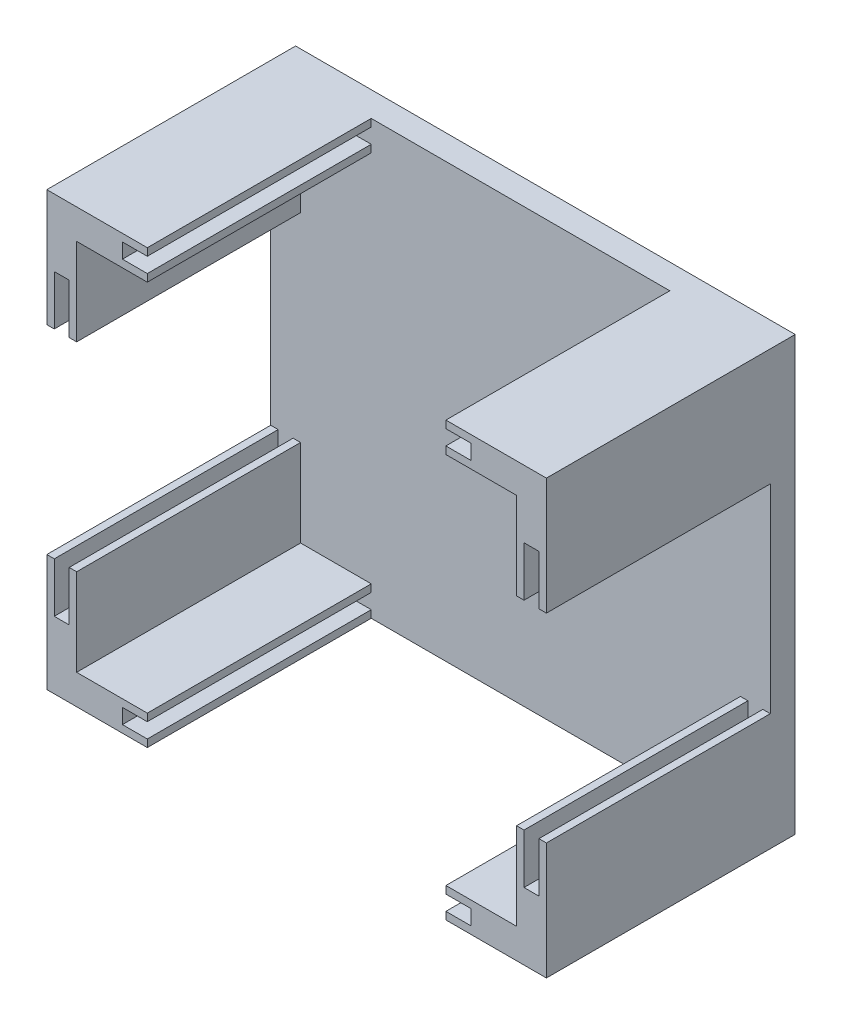
SolidWorks part; units mm, degrees
ref_plane "Plan de face" through (0, 0, 0) normal (0, 0, 1) x (1, 0, 0)
ref_plane "Plan de dessus" through (0, 0, 0) normal (0, 1, 0) x (1, 0, 0)
ref_plane "Plan de droite" through (0, 0, 0) normal (1, 0, 0) x (0, 0, -1)
sketch "Esquisse1" plane through (0, 0, 0) normal (0, 0, 1) x (1, 0, 0)
  line L0 (-50.2, 43.5) -> (50.2, 43.5)
  line L1 (-40.2, 33.5) -> (40.2, 33.5) construction
  line L2 (-40.2, 33.5) -> (-40.2, -33.5) construction
  line L3 (-40.2, -33.5) -> (40.2, -33.5) construction
  line L4 (40.2, 33.5) -> (40.2, -33.5) construction
  line L5 (-40.2, 33.5) -> (40.2, -33.5) construction
  line L6 (-40.2, -33.5) -> (40.2, 33.5) construction
  line L15 (50.2, 43.5) -> (50.2, -43.5)
  line L16 (-50.2, -43.5) -> (50.2, -43.5)
  line L17 (-50.2, 43.5) -> (-50.2, -43.5)
  point P0 (0, 0)
  point P5 (0, 0)
  dimension "D1" = 80.4
  dimension "D2" = 67
  dimension "D3" = 10
extrude "Boss.-Extru.1" add sketch "Esquisse1" along normal blind 50
sketch "Esquisse3" plane through (0, 0, 50) normal (0, 0, 1) x (1, 0, 0)
  line L8 (-44.2, 37.5) -> (-44.2, -37.5)
  line L9 (-44.2, -37.5) -> (44.2, -37.5)
  line L10 (44.2, -37.5) -> (44.2, 37.5)
  line L11 (44.2, 37.5) -> (-44.2, 37.5)
  line L12 (-44.2, 37.5) -> (-44.2, -37.5)
  line L13 (-44.2, -37.5) -> (44.2, -37.5)
  line L14 (44.2, -37.5) -> (44.2, 37.5)
  line L15 (44.2, 37.5) -> (-44.2, 37.5)
  dimension "D1" = 6
extrude "Enlèv. mat.-Extru.1" cut sketch "Esquisse3" against normal offset from surface (45 mm away) 5 up to face at (0, 0, 0)
sketch "Esquisse5" plane through (0, 0, 50) normal (0, 0, 1) x (1, 0, 0)
  line L0 (-44.2, 0) -> (-50.2, 0) construction
  line L1 (-48.7, 30) -> (-45.7, 30)
  line L2 (-48.7, 30) -> (-48.7, -30)
  line L3 (-48.7, -30) -> (-45.7, -30)
  line L4 (-45.7, 30) -> (-45.7, -30)
  line L5 (-48.7, 30) -> (-45.7, -30) construction
  line L6 (-48.7, -30) -> (-45.7, 30) construction
  line L7 (-44.2, 37.5) -> (-44.2, -37.5) construction
  line L8 (-50.2, 43.5) -> (-50.2, -43.5) construction
  point P0 (-47.2, 0)
  point P12 (-47.2, 0)
  dimension "D1" = 3
  dimension "D2" = 60
extrude "Enlèv. mat.-Extru.2" cut sketch "Esquisse5" against normal up to surface (45 mm away) up to face at (0, 0, 5)
mirror "Symétrie1" about plane through (0, 0, 0) normal (1, 0, 0) of "Enlèv. mat.-Extru.2"
sketch "Esquisse7" plane through (0, 0, 50) normal (0, 0, 1) x (1, 0, 0)
  line L0 (0, 43.5) -> (0, 37.5) construction
  line L1 (50.2, 43.5) -> (-50.2, 43.5) construction
  line L2 (-44.2, 37.5) -> (44.2, 37.5) construction
  line L4 (-35, 42) -> (35, 42)
  line L5 (-35, 42) -> (-35, 39)
  line L6 (-35, 39) -> (35, 39)
  line L7 (35, 42) -> (35, 39)
  line L8 (-35, 42) -> (35, 39) construction
  line L9 (-35, 39) -> (35, 42) construction
  point P6 (0, 40.5)
  dimension "D1" = 3
  dimension "D2" = 70
extrude "Enlèv. mat.-Extru.3" cut sketch "Esquisse7" against normal up to surface (45 mm away) up to face at (0, 0, 5)
mirror "Symétrie2" about plane through (0, 0, 0) normal (0, 1, 0) of "Enlèv. mat.-Extru.3"
sketch "Esquisse8" plane through (0, 0, 50) normal (0, 0, 1) x (1, 0, 0)
  line L0 (50.2, -43.5) -> (50.2, 43.5) construction
  line L1 (-50.2, 20) -> (50.2, 20)
  line L2 (-50.2, 20) -> (-50.2, -20)
  line L3 (-50.2, -20) -> (50.2, -20)
  line L4 (50.2, 20) -> (50.2, -20)
  line L5 (-50.2, 20) -> (50.2, -20) construction
  line L6 (-50.2, -20) -> (50.2, 20) construction
  line L7 (-45.7, 30) -> (-48.7, 30) construction
  point P0 (0, 0)
  dimension "D1" = 10
extrude "Enlèv. mat.-Extru.4" cut sketch "Esquisse8" against normal up to surface (45 mm away) up to face at (0, 0, 5)
sketch "Esquisse9" plane through (0, 0, 50) normal (0, 0, 1) x (1, 0, 0)
  line L0 (-50.2, -43.5) -> (50.2, -43.5) construction
  line L1 (-30, 43.5) -> (30, 43.5)
  line L2 (-30, 43.5) -> (-30, -43.5)
  line L3 (-30, -43.5) -> (30, -43.5)
  line L4 (30, 43.5) -> (30, -43.5)
  line L5 (-30, 43.5) -> (30, -43.5) construction
  line L6 (-30, -43.5) -> (30, 43.5) construction
  line L7 (35, 39) -> (35, 42) construction
  point P0 (0, 0)
  dimension "D1" = 5
extrude "Enlèv. mat.-Extru.5" cut sketch "Esquisse9" against normal up to surface (45 mm away) up to face at (0, 0, 5)
